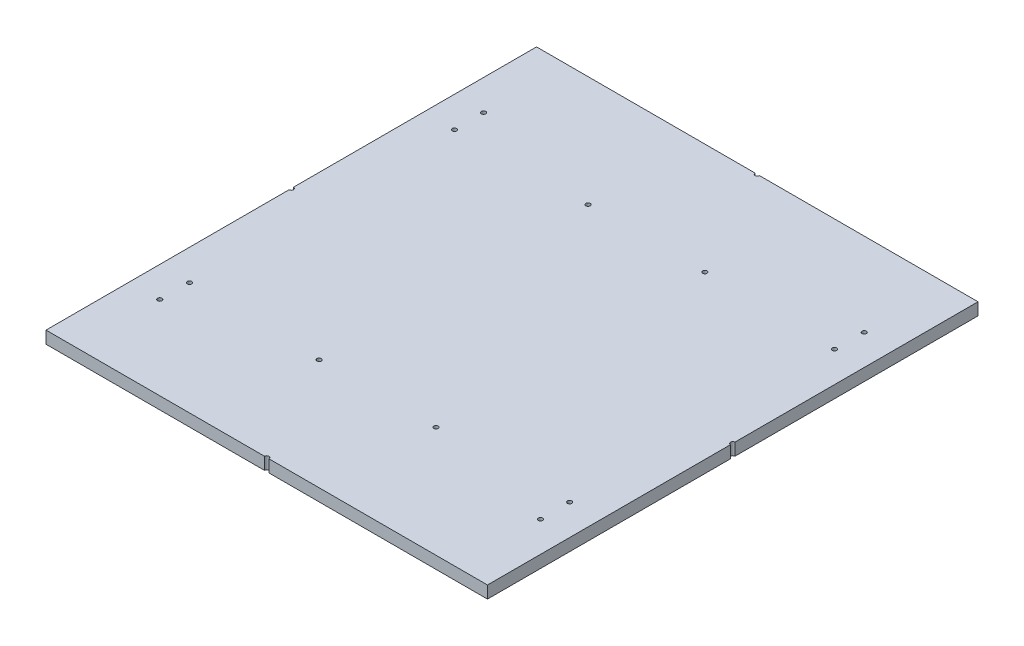
SolidWorks part; units mm, degrees
ref_plane "Front Plane" through (0, 0, 0) normal (0, 0, 1) x (1, 0, 0)
ref_plane "Top Plane" through (0, 0, 0) normal (0, 1, 0) x (1, 0, 0)
ref_plane "Right Plane" through (0, 0, 0) normal (1, 0, 0) x (0, 0, -1)
sketch "Sketch1" plane through (0, 0, 0) normal (0, 1, 0) x (1, 0, 0)
  line L1 (0, 0) -> (228.6, 0)
  line L2 (0, 0) -> (0, 254)
  line L3 (0, 254) -> (228.6, 254)
  line L4 (228.6, 0) -> (228.6, 254)
  dimension "D1" = 228.6
  dimension "D2" = 254
extrude "Boss-Extrude1" add sketch "Sketch1" along normal blind 6.35
hole_wizard "#4-40 Tapped Hole1" positions "Sketch2" profile "Sketch3" tap size "#4-40" standard "ANSI Inch" end condition through all
sketch "Sketch2" plane through (0, 6.35, 0) normal (0, 1, 0) x (1, 0, 0)
  line L0 (-228.6, 127) -> (228.6, 127) construction
  line L2 (228.6, 0) -> (228.6, 254) construction
  line L4 (114.3, -254) -> (114.3, 254) construction
  line L6 (228.6, 254) -> (0, 254) construction
  circle A0 centre (84.0588, 57.3884) radius 1.4224
  circle A1 centre (144.5617, 57.3884) radius 1.4224
  point P0 (15.7352, 43.18)
  point P3 (15.875, 58.42)
  point P7 (84.0588, 57.3884)
  point P10 (144.5617, 57.3884)
  point P89 (0, 127)
  point P92 (144.5617, 196.6116)
  point P93 (84.0588, 196.6116)
  point P94 (15.875, 195.58)
  point P95 (15.7352, 210.82)
  point P139 (114.3, 0)
  point P142 (212.8648, 43.18)
  point P143 (212.725, 58.42)
  point P144 (212.8648, 210.82)
  point P145 (212.725, 195.58)
  point P146 (228.6, 127)
  point P147 (114.3, 254)
  dimension "D2" = 2.8448
  dimension "D1" = 2.8448
sketch "Sketch3" plane through (15.7352, 6.35, -43.18) normal (1, 0, 0) x (0, 0, 1)
  line L0 (0, 0) -> (0, 6.35)
  line L1 (0, 6.35) -> (1.1303, 6.35)
  line L2 (1.1303, 6.35) -> (1.1303, 0)
  line L5 (1.1303, 0) -> (0, 0)
  line L11 (0, -6.35) -> (0, 107.95) construction
  dimension "Thru Tap Drill Dia." = 2.2606
  dimension "Thru Tap Drill Depth" = 6.35
cosmetic thread "Hole Thread1"
cosmetic thread "Hole Thread2"
cosmetic thread "Hole Thread3"
cosmetic thread "Hole Thread4"
cosmetic thread "Hole Thread5"
cosmetic thread "Hole Thread6"
cosmetic thread "Hole Thread7"
cosmetic thread "Hole Thread8"
cosmetic thread "Hole Thread9"
cosmetic thread "Hole Thread10"
cosmetic thread "Hole Thread11"
cosmetic thread "Hole Thread12"
cosmetic thread "Hole Thread13"
cosmetic thread "Hole Thread14"
cosmetic thread "Hole Thread15"
cosmetic thread "Hole Thread16"
